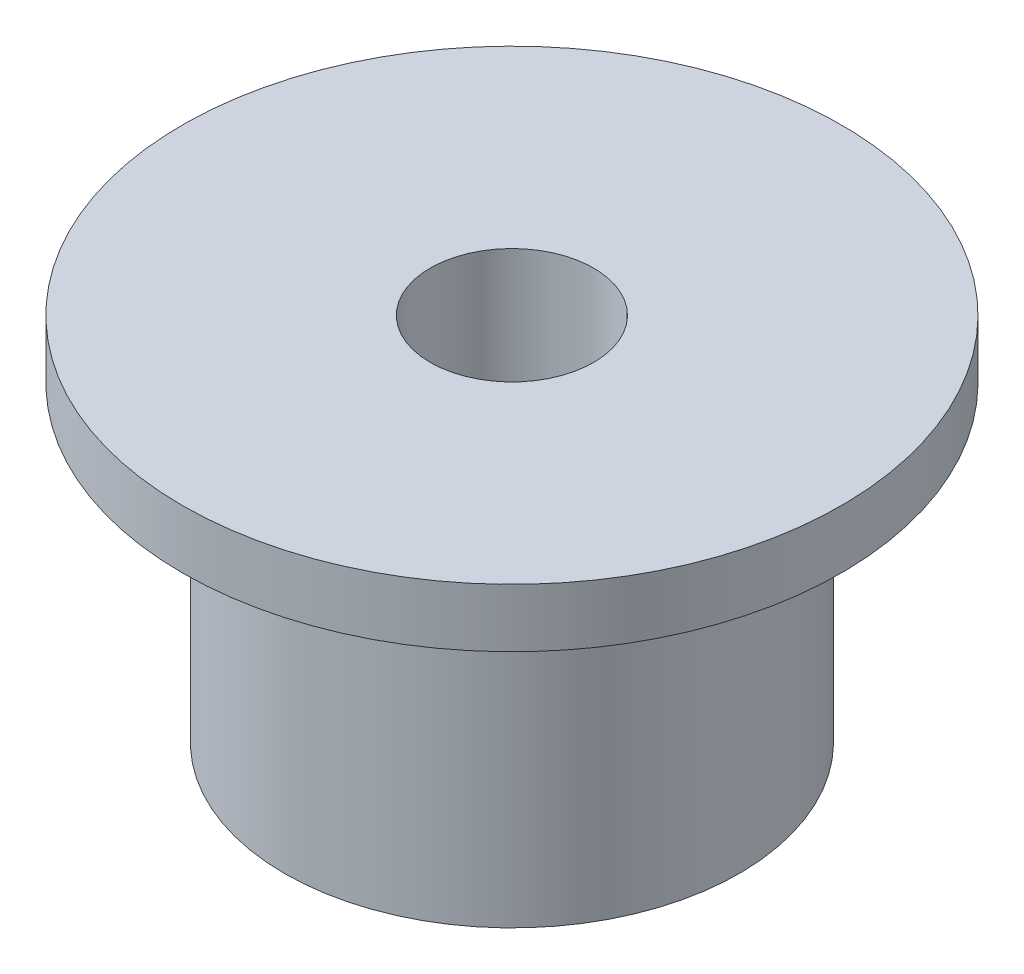
SolidWorks part; units mm, degrees
material "Natural Rubber"
ref_plane "Front Plane" through (0, 0, 0) normal (0, 0, 1) x (1, 0, 0)
ref_plane "Top Plane" through (0, 0, 0) normal (0, 1, 0) x (1, 0, 0)
ref_plane "Right Plane" through (0, 0, 0) normal (1, 0, 0) x (0, 0, -1)
sketch "Sketch1" plane through (0, 0, 0) normal (0, 1, 0) x (1, 0, 0)
  circle A0 centre (0, 0) radius 2.921
  dimension "D1" = 5.842
extrude "Boss-Extrude1" add sketch "Sketch1" along normal blind 4 contours A0
sketch "Sketch2" plane through (0, 4, 0) normal (0, 1, 0) x (1, 0, 0)
  circle A0 centre (0, 0) radius 4.2333
  dimension "D1" = 8.4667
extrude "Boss-Extrude2" add sketch "Sketch2" along normal blind 0.75 contours A0
sketch "Sketch3" plane through (0, 4.75, 0) normal (0, 1, 0) x (1, 0, 0)
  circle A0 centre (0, 0) radius 1.05
extrude "Cut-Extrude1" cut sketch "Sketch3" against normal through all
